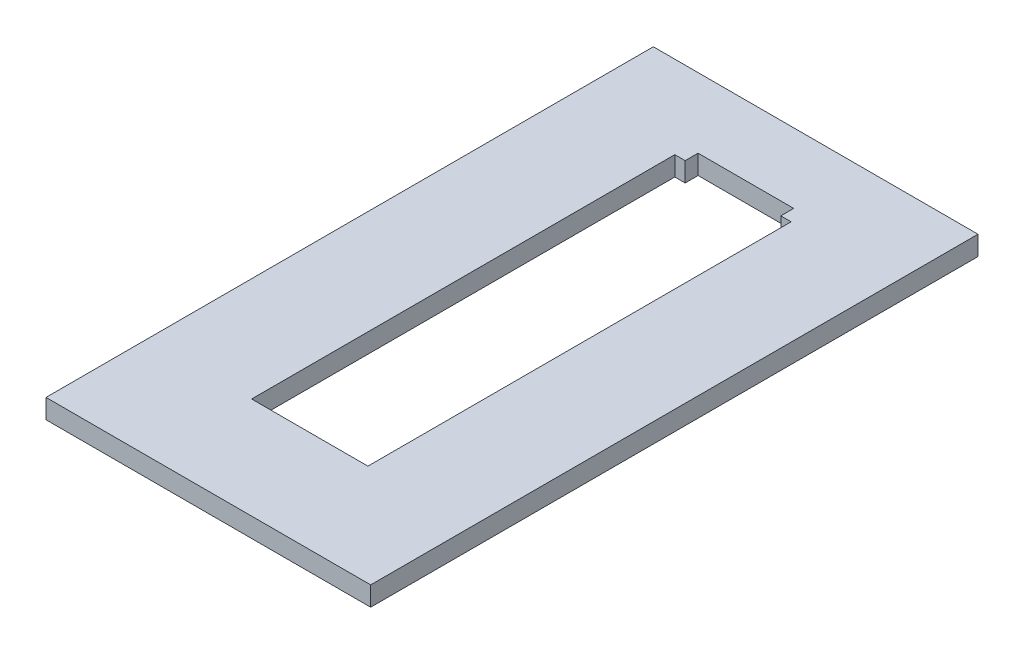
SolidWorks part; units mm, degrees
material "Щебень 40-20"
ref_plane "Спереди" through (0, 0, 0) normal (0, 0, 1) x (1, 0, 0)
ref_plane "Сверху" through (0, 0, 0) normal (0, 1, 0) x (1, 0, 0)
ref_plane "Справа" through (0, 0, 0) normal (1, 0, 0) x (0, 0, -1)
sketch "Эскиз1" plane through (0, 0, 0) normal (0, 1, 0) x (1, 0, 0)
  line L0 (-740, 3620) -> (740, 3620) construction
  line L1 (-2512.5, 4700) -> (2512.5, 4700)
  line L2 (-2512.5, 4700) -> (-2512.5, -4700)
  line L3 (-2512.5, -4700) -> (2512.5, -4700)
  line L4 (2512.5, 4700) -> (2512.5, -4700)
  line L5 (900, -3130) -> (-900, -3130)
  line L6 (900, -3130) -> (900, 3420)
  line L7 (740, 3620) -> (-740, 3620)
  line L8 (-900, -3130) -> (-900, 3420)
  line L9 (-900, 3420) -> (-900, 2220) construction
  line L10 (-740, 3420) -> (-740, 3620)
  line L11 (-740, 3420) -> (-900, 3420)
  line L12 (740, 3420) -> (740, 3620)
  line L13 (740, 3420) -> (900, 3420)
extrude "Бобышка-Вытянуть1" add sketch "Эскиз1" along normal up to surface (300 mm away)
